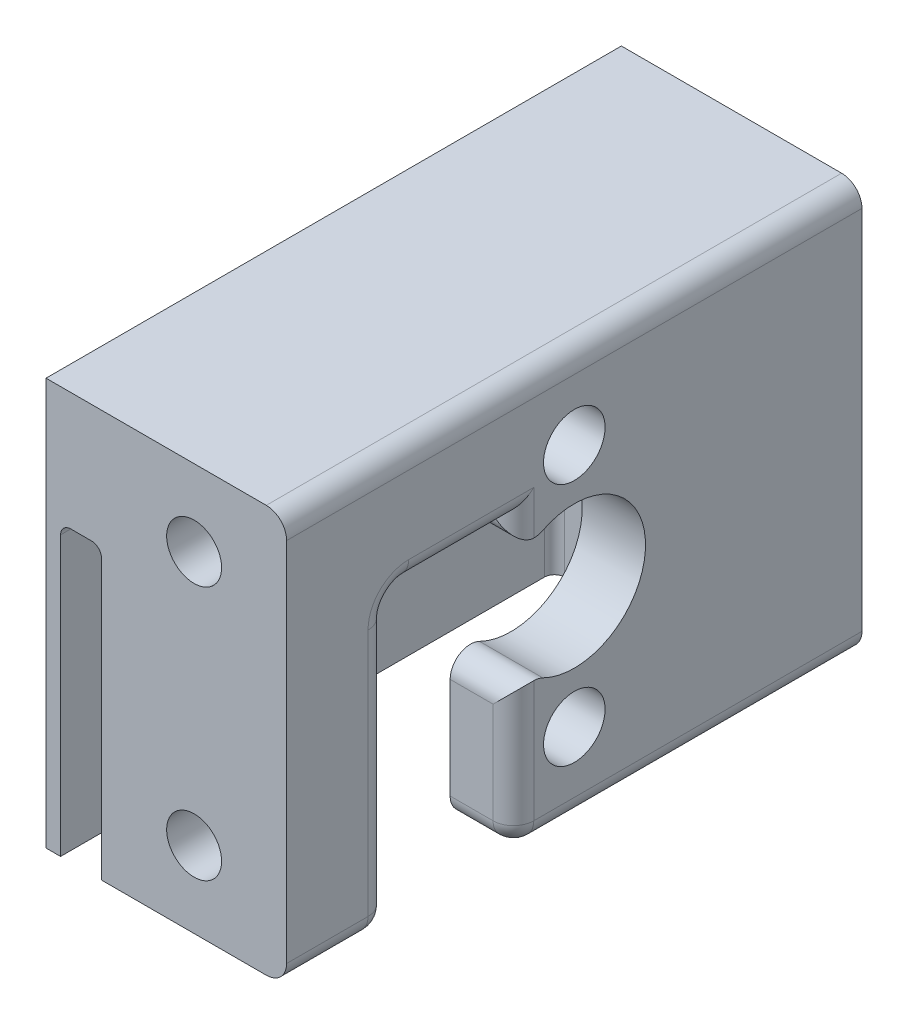
SolidWorks part; units mm, degrees
material "ABS"
ref_plane "X-Y Datum" through (0, 0, 0) normal (0, 0, 1) x (1, 0, 0)
ref_plane "X-Z Datum" through (0, 0, 0) normal (0, 1, 0) x (1, 0, 0)
ref_plane "Y-Z Datum" through (0, 0, 0) normal (1, 0, 0) x (0, 0, -1)
sketch "Sketch1" plane through (0, 0, 0) normal (0, 0, 1) x (1, 0, 0)
  line L1 (-11.825, 20) -> (11.825, 20)
  line L2 (-11.825, 20) -> (-11.825, -20)
  line L3 (-11.825, -20) -> (11.825, -20)
  line L4 (11.825, 20) -> (11.825, -20)
  line L5 (-11.825, 20) -> (11.825, -20) construction
  line L6 (-11.825, -20) -> (11.825, 20) construction
  point P0 (0, 0)
  dimension "D1" = 23.65
  dimension "D2" = 40
extrude "Boss-Extrude1" add sketch "Sketch1" along normal blind 56.55
sketch "Sketch2" plane through (0, 0, 56.55) normal (0, 0, 1) x (1, 0, 0)
  line L0 (-9.3955, -7.38) -> (-7.3635, -7.38) construction
  line L1 (-7.3635, -7.38) -> (-7.3635, 7.38) construction
  line L2 (-9.3955, 7.38) -> (-7.3635, 7.38) construction
  line L3 (-9.3955, 7.38) -> (-9.3955, -7.38) construction
  line L4 (-9.3955, -7.38) -> (-7.3635, -7.38)
  line L5 (-7.3635, -7.38) -> (-7.3635, 7.38)
  line L6 (-9.3955, 7.38) -> (-7.3635, 7.38)
  line L7 (-9.3955, 7.38) -> (-9.3955, -7.38)
  line L12 (-10.3955, -7.38) -> (-10.3955, -20)
  line L13 (-11.825, -20) -> (11.825, -20) construction
  line L14 (-7.3635, 8.38) -> (5.6045, 8.38)
  line L15 (5.6045, 8.38) -> (5.6045, -20)
  line L16 (-6.3635, -7.38) -> (-6.3635, 8.38) construction
  line L17 (-10.3955, 8.38) -> (-7.3635, 8.38)
  line L18 (-9.3955, 8.38) -> (-7.3635, 8.38) construction
  line L19 (-10.3955, 8.38) -> (-10.3955, -7.38)
  line L21 (-6.3635, -20) -> (-6.3635, 8.38)
  line L22 (-9.3955, 8.38) -> (-6.3635, 8.38) construction
  line L23 (-10.3955, 7.38) -> (-10.3955, -7.38) construction
  dimension "D2" = 16
  dimension "D1" = 1
  dimension "D3" = 1
  dimension "D4" = 1
extrude "Cut-Extrude1" cut sketch "Sketch2" against normal through all
sketch "Sketch3" plane through (11.825, 0, 0) normal (1, 0, 0) x (0, 0, -1)
  line L0 (-28.275, 20) -> (-28.275, -20) construction
  line L1 (-56.55, 20) -> (0, 20) construction
  line L2 (-56.55, -20) -> (0, -20) construction
  circle A0 centre (-28.275, 0) radius 7
  dimension "D1" = 14
extrude "Cut-Extrude2" cut sketch "Sketch3" against normal up to surface (6.2205 mm away) up to face at (5.6045, -5.81, 28.275)
sketch "Sketch6" plane through (11.825, 0, 0) normal (1, 0, 0) x (0, 0, -1)
  circle A0 centre (-28.275, -12) radius 2 construction
  circle A1 centre (-28.275, 12) radius 2 construction
  circle A2 centre (-28.275, -12) radius 2 construction
  circle A3 centre (-28.275, 12) radius 2 construction
  circle A4 centre (-28.275, 12) radius 3.025
  circle A5 centre (-28.275, -12) radius 3.025
  dimension "D1" = 6.05
extrude "Cut-Extrude4" cut sketch "Sketch6" against normal blind 8 contours A4 | A5
sketch "Sketch4" plane through (0, 8.38, 0) normal (0, -1, 0) x (1, 0, 0)
  line L0 (-7.3635, 61.468) -> (-7.3635, 34.29) construction
  line L1 (-7.3635, 61.468) -> (-7.3635, 34.29) construction
  line L2 (-7.3635, 46.55) -> (5.6045, 46.55)
  line L3 (-6.3635, 61.468) -> (-6.3635, 34.29)
  line L4 (5.6045, 56.55) -> (-10.3955, 56.55)
  line L5 (-10.3955, 56.55) -> (-10.3955, 0)
  line L6 (-10.3955, 0) -> (5.6045, 0)
  line L7 (5.6045, 0) -> (5.6045, 56.55)
  line L8 (5.6045, 56.55) -> (-10.3955, 56.55)
  line L9 (-10.3955, 56.55) -> (-10.3955, 0)
  line L10 (-10.3955, 0) -> (5.6045, 0)
  line L11 (5.6045, 0) -> (5.6045, 56.55)
  dimension "D2" = 10
  dimension "D1" = 0
  dimension "D3" = 1
extrude "Boss-Extrude2" add sketch "Sketch4" along normal up to surface (28.38 mm away) up to face at (8.7147, -20, 28.275)
sketch "Sketch5" plane through (11.825, 0, 0) normal (1, 0, 0) x (0, 0, -1)
  line L0 (-32.258, 4.84) -> (-32.258, -4.84) construction
  line L1 (-32.258, 20) -> (-32.258, -20) construction
  line L2 (-56.55, -20) -> (0, -20) construction
  line L3 (-56.55, 20) -> (0, 20) construction
  line L4 (-56.55, 0) -> (0, 0)
  line L5 (0, 8.38) -> (-46.55, 8.38) construction
  line L6 (-34.258, 20) -> (-34.258, -20)
  line L7 (-46.55, -20) -> (-46.55, 8.38) construction
  line L8 (-46.55, -20) -> (-46.55, 8.38)
  line L9 (0, -20) -> (0, 20)
  line L10 (0, 20) -> (-56.55, 20)
  line L11 (-56.55, 20) -> (-56.55, -20)
  line L12 (-56.55, -20) -> (0, -20)
  line L13 (0, -20) -> (0, 20)
  line L14 (0, 20) -> (-56.55, 20)
  line L15 (-56.55, 20) -> (-56.55, -20)
  line L16 (-56.55, -20) -> (0, -20)
  line L17 (0, 8.38) -> (-46.55, 8.38)
  point P15 (-32.258, 0)
  dimension "D1" = 0
  dimension "D2" = 2
extrude "Cut-Extrude3" cut sketch "Sketch5" against normal up to surface (6.2205 mm away)
fillet "Fillet5" radius 2 1 edges at (5.6045, 8.38, 17.129)
sketch "Sketch9" plane through (-10.3955, 0, 0) normal (1, 0, 0) x (0, 0, -1)
  line L1 (0, -20) -> (-8, -20)
  line L2 (0, -20) -> (0, -9)
  line L3 (0, -9) -> (-8, -9)
  line L4 (-8, -20) -> (-8, -9)
  dimension "D1" = 8
  dimension "D2" = 11
extrude "Boss-Extrude3" add sketch "Sketch9" along normal up to surface (16 mm away) up to face at (5.6045, -15.025, 28.275)
sketch "Sketch8" plane through (0, 0, 0) normal (0, 0, -1) x (-1, 0, 0)
  line L0 (0, 20) -> (0, 8.38) construction
  line L1 (-11.825, 20) -> (11.825, 20) construction
  line L2 (10.3955, 8.38) -> (-3.6045, 8.38) construction
  line L3 (-7.6296, 14.19) -> (7.6296, 14.19) construction
  line L4 (0, -20) -> (0, -9) construction
  line L5 (11.825, -20) -> (-11.825, -20) construction
  line L6 (-5.6045, -9) -> (10.3955, -9) construction
  line L7 (-4.1387, -14.5) -> (4.1387, -14.5) construction
  circle A0 centre (0, 14.19) radius 2.7
  circle A1 centre (0, -14.5) radius 2.7
  point P9 (0, 14.19)
  point P20 (0, -14.5)
  dimension "D1" = 5.4
extrude "Cut-Extrude6" cut sketch "Sketch8" against normal blind 9
sketch "Sketch7" plane through (0, 0, 56.55) normal (0, 0, 1) x (1, 0, 0)
  line L0 (2.7307, -20) -> (2.7307, 20) construction
  line L1 (-6.3635, -20) -> (11.825, -20) construction
  line L2 (11.825, 20) -> (-11.825, 20) construction
  line L3 (2.7307, 12.5) -> (2.7307, -12.5) construction
  circle A0 centre (2.7307, 12.5) radius 2.7
  circle A1 centre (2.7307, -12.5) radius 2.7
  point P11 (2.7307, 0)
  dimension "D1" = 5.4
  dimension "D2" = 25
extrude "Cut-Extrude5" cut sketch "Sketch7" against normal blind 8
fillet "Fillet4" radius 2 14 edges at (5.6045, -14.5, 8) (5.6045, -9, 4) (2.7308, -20, 46.55) (2.7308, 8.38, 46.55) (8.7147, 3.6337, 34.258) (8.7147, -3.6337, 34.258) (11.825, -20, 17.129) (11.825, 8.38, 40.404) (11.825, -11.8168, 34.258) (11.825, 6.0068, 34.258) (11.825, -5.81, 46.55) (8.7147, -20, 34.258) (11.825, -20, 51.55) (11.825, 20, 28.275)
sketch "Sketch10" [suppressed] plane through (0, 8.38, 0) normal (0, -1, 0) x (1, 0, 0)
  line L0 (-7.3635, 22.86) -> (-7.3635, -4.318) construction
  line L1 (-7.3635, 22.86) -> (-7.3635, -4.318) construction
  line L2 (-6.3635, 22.86) -> (-6.3635, -4.318)
  line L3 (5.6045, 0) -> (5.6045, 56.55) construction
  line L4 (5.6045, 0) -> (5.6045, 56.55)
  line L5 (5.6045, 10) -> (-6.3635, 10)
  line L6 (-10.3955, 0) -> (5.6045, 0) construction
  dimension "D2" = 10
  dimension "D1" = 1
extrude "Boss-Extrude4" [suppressed] add sketch "Sketch10" along normal up to surface (28.38 mm away)
sketch "Sketch11" [suppressed] plane through (11.825, 0, 0) normal (1, 0, 0) x (0, 0, -1)
  line L1 (-22.892, 8.38) -> (-22.892, -20)
  line L2 (-24.892, 4.84) -> (-24.892, -4.84) construction
  line L3 (-24.892, 4.84) -> (-24.892, -4.84) construction
  line L4 (-22.892, 4.84) -> (-22.892, -4.84) construction
  line L5 (-56.55, -20) -> (0, -20) construction
  line L6 (-10, -20) -> (-10, 8.38) construction
  line L7 (-10, -20) -> (-10, 8.38)
  line L8 (-10, 8.38) -> (-56.55, 8.38) construction
  line L9 (-10, 8.38) -> (-56.55, 8.38)
  dimension "D1" = 2
extrude "Cut-Extrude7" [suppressed] cut sketch "Sketch11" against normal up to surface (6.2205 mm away)
fillet "Fillet6" [suppressed] radius 2
sketch "Sketch12" [suppressed] plane through (-10.3955, 0, 0) normal (1, 0, 0) x (0, 0, -1)
  line L1 (-56.55, -20) -> (-48.55, -20)
  line L2 (-56.55, -20) -> (-56.55, -9)
  line L3 (-56.55, -9) -> (-48.55, -9)
  line L4 (-48.55, -20) -> (-48.55, -9)
  dimension "D1" = 8
  dimension "D2" = 11
extrude "Boss-Extrude5" [suppressed] add sketch "Sketch12" along normal up to surface (16 mm away)
sketch "Sketch13" [suppressed] plane through (0, 0, 0) normal (0, 0, -1) x (-1, 0, 0)
  circle A0 centre (-2.7308, -12.038) radius 2.7
  circle A1 centre (-2.7308, 12.962) radius 2.7
  point P0 (-2.7308, -12.038)
  point P1 (-2.7308, 12.962)
  dimension "D1" = 5.4
extrude "Cut-Extrude8" [suppressed] cut sketch "Sketch13" against normal blind 8
sketch "Sketch14" [suppressed] plane through (0, 0, 56.55) normal (0, 0, 1) x (1, 0, 0)
  circle A0 centre (0, -14.038) radius 2.7
  circle A1 centre (0, 14.652) radius 2.7
  point P0 (0, -14.038)
  point P1 (0, 14.652)
  dimension "D1" = 5.4
extrude "Cut-Extrude9" [suppressed] cut sketch "Sketch14" against normal blind 9
fillet "Fillet7" [suppressed] radius 2
fillet "Fillet8" radius 1 4 edges at (-10.3955, 8.38, 28.275) (-6.3635, 8.38, 50.55) (-10.3955, -9, 4) (-10.3955, -14.5, 8)
fillet "Fillet9" [suppressed] radius 1
